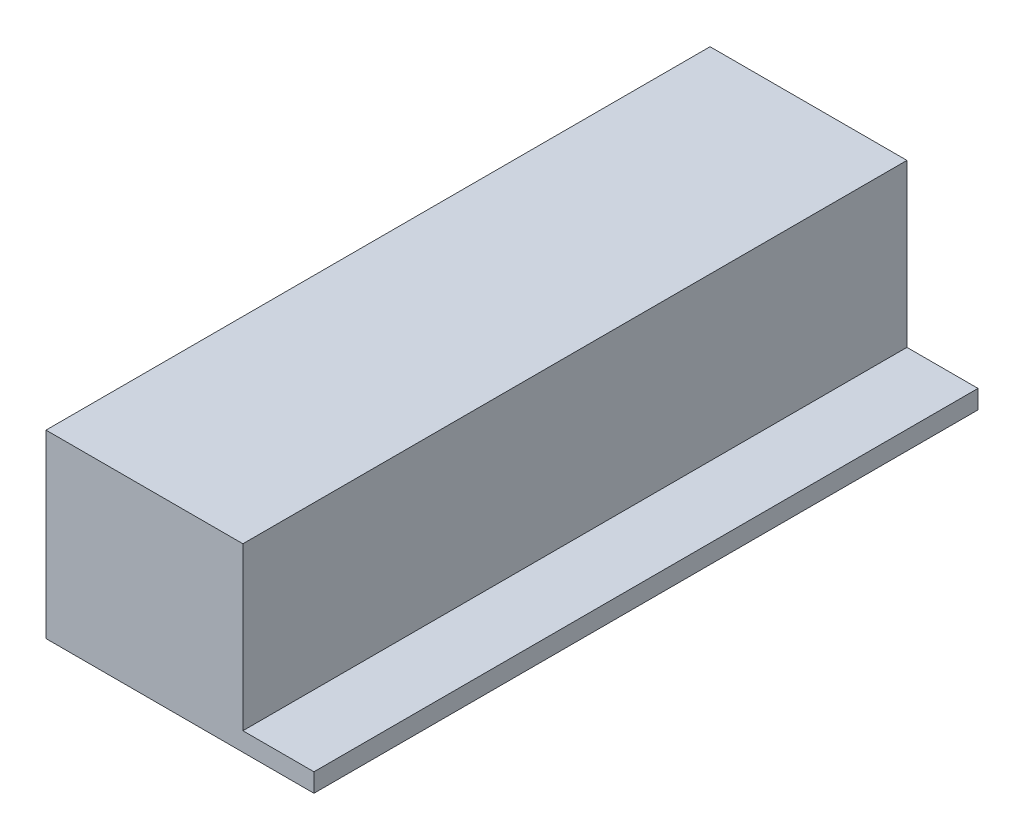
SolidWorks part; units mm, degrees
ref_plane "Front" through (0, 0, 0) normal (0, 0, 1) x (1, 0, 0)
ref_plane "Top" through (0, 0, 0) normal (0, 1, 0) x (1, 0, 0)
ref_plane "Right" through (0, 0, 0) normal (1, 0, 0) x (0, 0, -1)
sketch "Sketch1" plane through (0, 0, 0) normal (0, 0, 1) x (1, 0, 0)
  line L0 (0, 0) -> (23, 0)
  line L1 (23, 0) -> (23, 1.6)
  line L2 (23, 1.6) -> (16.9, 1.6)
  line L3 (16.9, 1.6) -> (16.9, 15.5)
  line L4 (16.9, 15.5) -> (0, 15.5)
  line L5 (0, 15.5) -> (0, 0)
  dimension "D1" = 23
  dimension "D2" = 1.6
  dimension "D3" = 13.9
  dimension "D4" = 16.9
extrude "Boss-Extrude1" add sketch "Sketch1" along normal blind 57
